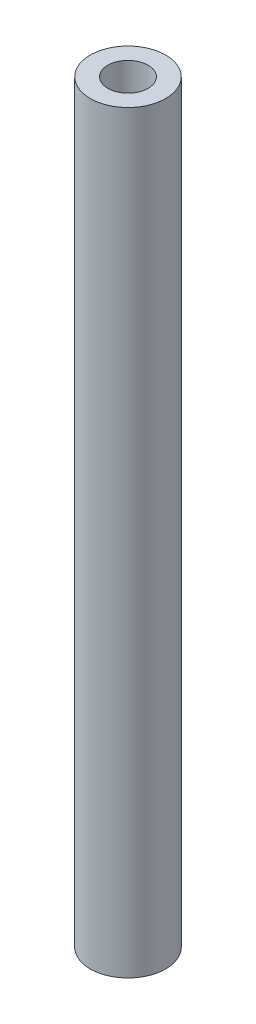
SolidWorks part; units mm, degrees
ref_plane "Front Plane" through (0, 0, 0) normal (0, 0, 1) x (1, 0, 0)
ref_plane "Top Plane" through (0, 0, 0) normal (0, 1, 0) x (1, 0, 0)
ref_plane "Right Plane" through (0, 0, 0) normal (1, 0, 0) x (0, 0, -1)
sketch "Sketch1" plane through (0, 0, 0) normal (0, 1, 0) x (1, 0, 0)
  circle A0 centre (0, 0) radius 6.35
  dimension "D1" = 12.7
extrude "Boss-Extrude2" add sketch "Sketch1" along normal blind 127 contours A0
sketch "Sketch2" plane through (0, 127, 0) normal (0, 1, 0) x (1, 0, 0)
  circle A0 centre (0, 0) radius 3.3895
extrude "Cut-Extrude1" cut sketch "Sketch2" against normal blind 134.62
